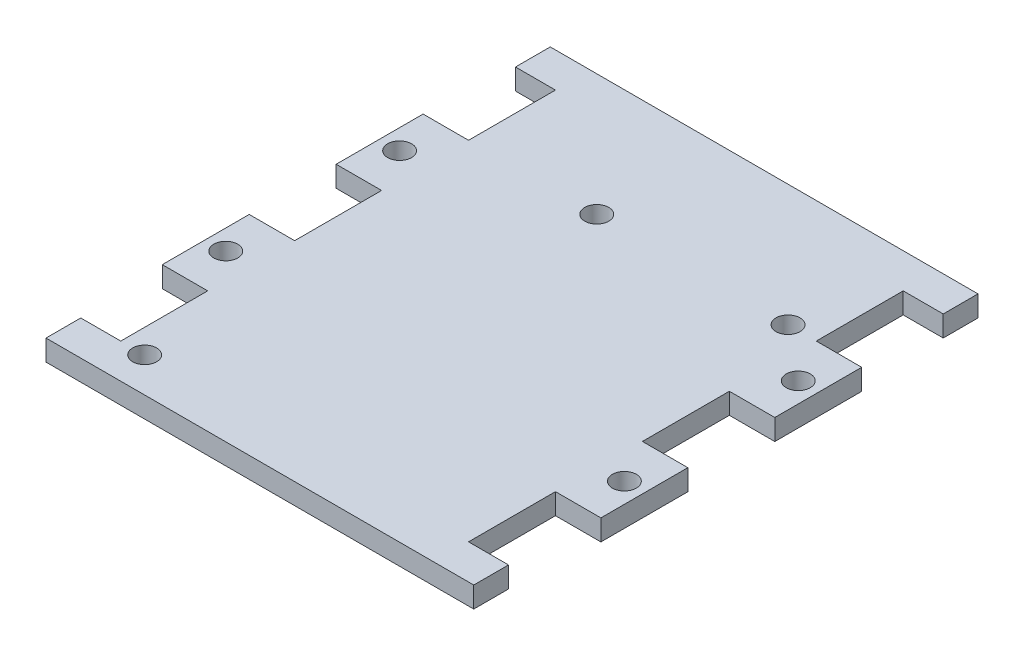
SolidWorks part; units mm, degrees
ref_plane "Front Plane" through (0, 0, 0) normal (0, 0, 1) x (1, 0, 0)
ref_plane "Top Plane" through (0, 0, 0) normal (0, 1, 0) x (1, 0, 0)
ref_plane "Right Plane" through (0, 0, 0) normal (1, 0, 0) x (0, 0, -1)
sketch "Sketch1" plane through (0, 0, 0) normal (0, 1, 0) x (1, 0, 0)
  line L0 (-31.242, -19.05) -> (-32.0358, -6.35) construction
  line L1 (31.242, -36.83) -> (-31.242, -36.83)
  line L2 (31.242, -36.83) -> (31.242, -31.75)
  line L3 (31.242, 36.83) -> (-31.242, 36.83)
  line L4 (-31.242, -36.83) -> (-31.242, -31.75)
  line L5 (0, 36.83) -> (0, -36.83) construction
  line L6 (31.242, 0) -> (-31.242, 0) construction
  line L7 (-25.4, -6.35) -> (-31.242, -6.35)
  line L8 (-25.4, -6.35) -> (-25.4, 6.35)
  line L9 (-25.4, 6.35) -> (-31.242, 6.35)
  line L10 (-25.4, -31.75) -> (-31.242, -31.75)
  line L11 (-28.321, 6.35) -> (-28.321, -6.35) construction
  line L12 (-25.4, 0) -> (-31.242, 0) construction
  line L13 (-25.4, -31.75) -> (-25.4, -19.05)
  line L14 (-25.4, -19.05) -> (-31.242, -19.05)
  line L15 (-28.321, -19.05) -> (-28.321, -31.75) construction
  line L16 (-25.4, -25.4) -> (-31.242, -25.4) construction
  line L17 (31.242, 6.35) -> (32.0358, 6.35)
  line L18 (-25.4, 25.4) -> (-31.242, 25.4) construction
  line L19 (-28.321, 19.05) -> (-28.321, 31.75) construction
  line L20 (-25.4, 19.05) -> (-31.242, 19.05)
  line L21 (-25.4, 31.75) -> (-25.4, 19.05)
  line L22 (-25.4, 31.75) -> (-31.242, 31.75)
  line L23 (-31.242, 31.75) -> (-31.242, 36.83)
  line L24 (-31.242, 12.7) -> (-25.4, 12.7) construction
  line L25 (28.321, 19.05) -> (28.321, 31.75) construction
  line L26 (25.4, 25.4) -> (31.242, 25.4) construction
  line L27 (25.4, -25.4) -> (31.242, -25.4) construction
  line L28 (28.321, -19.05) -> (28.321, -31.75) construction
  line L29 (25.4, 0) -> (31.242, 0) construction
  line L30 (28.321, 6.35) -> (28.321, -6.35) construction
  line L31 (25.4, 31.75) -> (31.242, 31.75)
  line L32 (25.4, 31.75) -> (25.4, 19.05)
  line L33 (25.4, 19.05) -> (31.242, 19.05)
  line L34 (25.4, -19.05) -> (31.242, -19.05)
  line L35 (25.4, -31.75) -> (25.4, -19.05)
  line L36 (25.4, -31.75) -> (31.242, -31.75)
  line L37 (25.4, 6.35) -> (31.242, 6.35)
  line L38 (25.4, -6.35) -> (25.4, 6.35)
  line L39 (25.4, -6.35) -> (31.242, -6.35)
  line L40 (31.242, 12.7) -> (25.4, 12.7) construction
  line L41 (31.242, 31.75) -> (31.242, 36.83)
  line L44 (-32.0358, -6.35) -> (-32.0358, -19.05)
  line L45 (-31.242, 19.05) -> (-32.0358, 19.05)
  line L46 (-31.242, -6.35) -> (-32.0358, -19.05) construction
  line L47 (-31.242, 6.35) -> (-32.0358, 6.35)
  line L48 (-32.0358, 19.05) -> (-32.0358, 6.35)
  line L49 (-31.242, 19.05) -> (-32.0358, 6.35) construction
  line L50 (-31.242, 6.35) -> (-32.0358, 19.05) construction
  line L51 (-31.242, -19.05) -> (-32.0358, -19.05)
  line L52 (-31.242, -6.35) -> (-32.0358, -6.35)
  line L53 (31.242, 6.35) -> (32.0358, 19.05) construction
  line L54 (31.242, 19.05) -> (32.0358, 6.35) construction
  line L55 (32.0358, 19.05) -> (32.0358, 6.35)
  line L56 (31.242, 19.05) -> (32.0358, 19.05)
  line L57 (31.242, -19.05) -> (32.0358, -19.05)
  line L58 (31.242, -6.35) -> (32.0358, -6.35)
  line L59 (31.242, -6.35) -> (32.0358, -19.05) construction
  line L60 (31.242, -19.05) -> (32.0358, -6.35) construction
  line L61 (32.0358, -6.35) -> (32.0358, -19.05)
  circle A0 centre (-29.1147, 12.7) radius 1.7526
  circle A1 centre (-29.1147, -12.7) radius 1.7526
  circle A2 centre (29.1147, -12.7) radius 1.7526
  circle A3 centre (29.1147, 12.7) radius 1.7526
  point P0 (0, 0)
  point P4 (-28.321, 0)
  point P9 (-28.321, -25.4)
  point P25 (-28.321, 25.4)
  point P67 (28.321, 25.4)
  point P68 (28.321, -25.4)
  point P69 (28.321, 0)
  point P76 (-31.6389, 12.7)
  dimension "D6" = 3.5052
  dimension "D1" = 62.484
  dimension "D2" = 73.66
  dimension "D3" = 5.842
  dimension "D4" = 12.7
  dimension "D7" = 0.7937
  dimension "D9" = 0.7937
  dimension "D5" = 2
  dimension "D8" = 2
  dimension "D10" = 2
extrude "Boss-Extrude1" add sketch "Sketch1" along normal blind 3.048
sketch "Sketch2" plane through (0, 3.048, 0) normal (0, 1, 0) x (1, 0, 0)
  line L0 (25.4, 19.05) -> (25.4, 31.75) construction
  circle A0 centre (21.2725, 19.05) radius 1.7526
  circle A1 centre (29.1147, 12.7) radius 1.7526 construction
  circle A2 centre (-6.6675, 19.05) radius 1.7526
  circle A3 centre (-21.9075, -31.75) radius 1.7526
  dimension "D1" = 3.5052
  dimension "D5" = 3.5052
  dimension "D2" = 4.1275
  dimension "D3" = 6.35
  dimension "D6" = 15.24
  dimension "D7" = 50.8
  dimension "D4" = 2
extrude "Cut-Extrude1" cut sketch "Sketch2" against normal through all
sketch "Sketch3" plane through (0, 3.048, 0) normal (0, 1, 0) x (1, 0, 0)
  circle A0 centre (-21.9075, -31.75) radius 3.175
  circle A1 centre (-21.9075, -31.75) radius 1.7526
  dimension "D1" = 6.35
extrude "Boss-Extrude2" [suppressed] add sketch "Sketch3" against normal up to surface (3.048 mm away)
